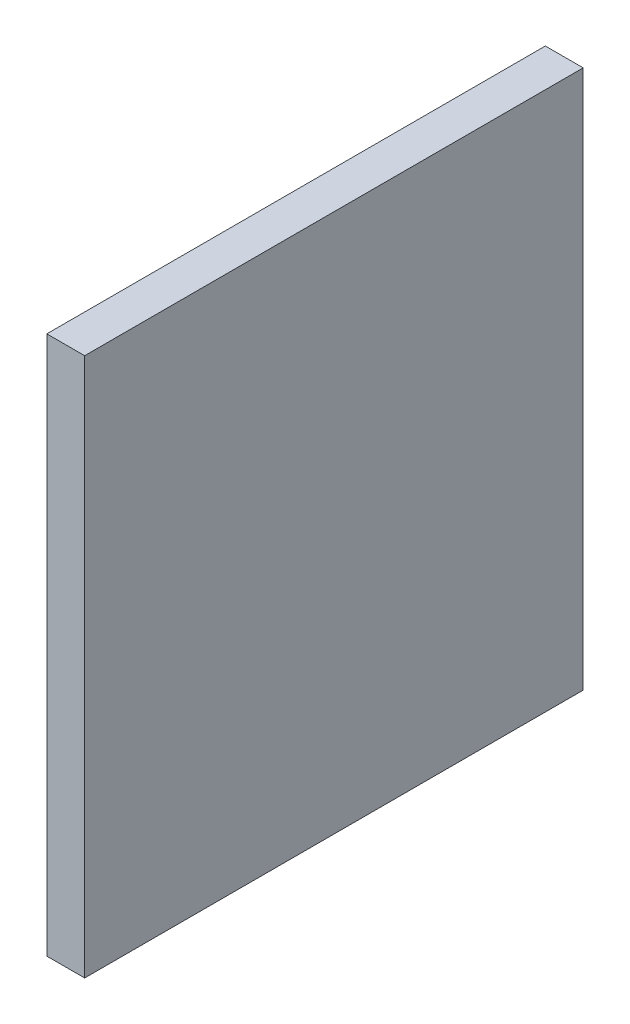
SolidWorks part; units mm, degrees
ref_plane "Front Plane" through (0, 0, 0) normal (0, 0, 1) x (1, 0, 0)
ref_plane "Top Plane" through (0, 0, 0) normal (0, 1, 0) x (1, 0, 0)
ref_plane "Right Plane" through (0, 0, 0) normal (1, 0, 0) x (0, 0, -1)
sketch "Sketch1" plane through (0, 0, 0) normal (1, 0, 0) x (0, 0, -1)
  line L1 (0, 0) -> (79, 0)
  line L2 (0, 0) -> (0, 85.4)
  line L3 (0, 85.4) -> (79, 85.4)
  line L4 (79, 0) -> (79, 85.4)
  dimension "D1" = 79
  dimension "D2" = 85.4
extrude "Boss-Extrude1" add sketch "Sketch1" along normal blind 6
